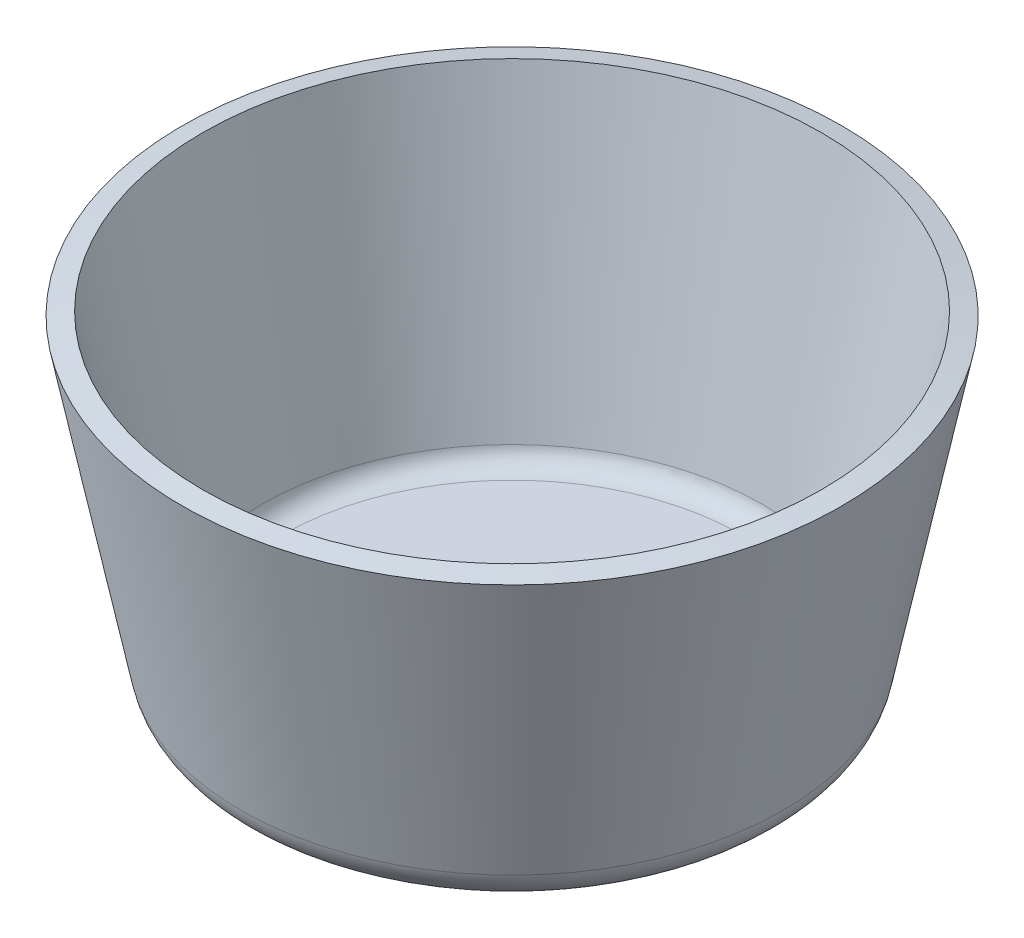
SolidWorks part; units mm, degrees
ref_plane "前视基准面" through (0, 0, 0) normal (0, 0, 1) x (1, 0, 0)
ref_plane "上视基准面" through (0, 0, 0) normal (0, 1, 0) x (1, 0, 0)
ref_plane "右视基准面" through (0, 0, 0) normal (1, 0, 0) x (0, 0, -1)
sketch "草图2" plane through (0, 0, 0) normal (1, 0, 0) x (0, 0, -1)
  line L0 (0, 0) -> (111.802, 0)
  line L1 (121.6078, 8.0388) -> (150, 150)
  line L2 (0, 0) -> (0, 140.7964) construction
  arc A0 (111.802, 0) -> (121.6078, 8.0388) centre (111.802, 10) ccw
  point P7 (120, 0)
  dimension "D4" = 10
  dimension "D1" = 150
  dimension "D2" = 120
  dimension "D3" = 150
revolve "旋转-薄壁3" add sketch "草图2" angle 360 about L2
